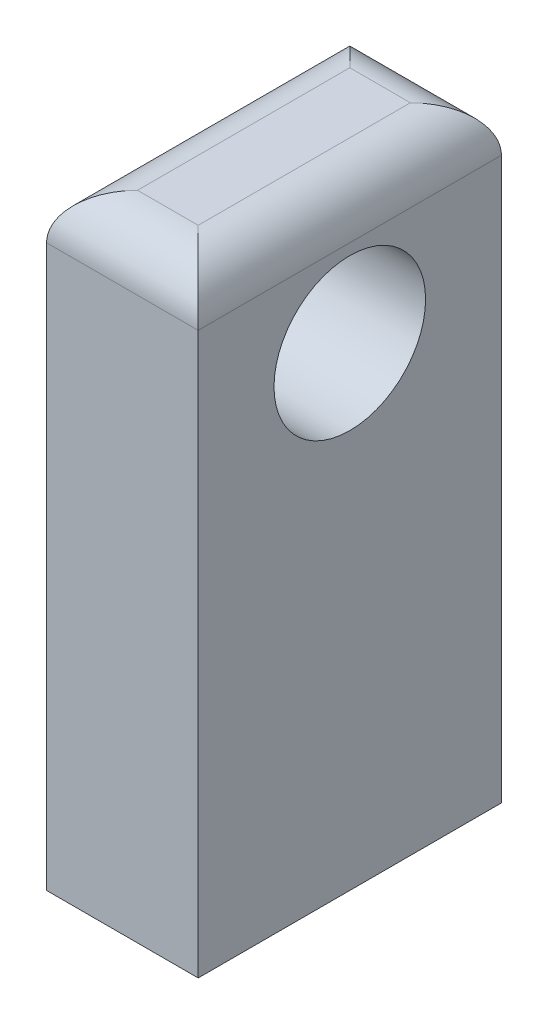
SolidWorks part; units mm, degrees
ref_plane "Front Plane" through (0, 0, 0) normal (0, 0, 1) x (1, 0, 0)
ref_plane "Top Plane" through (0, 0, 0) normal (0, 1, 0) x (1, 0, 0)
ref_plane "Right Plane" through (0, 0, 0) normal (1, 0, 0) x (0, 0, -1)
sketch "Sketch1" plane through (0, 0, 0) normal (1, 0, 0) x (0, 0, -1)
  line L1 (-10, 20) -> (10, 20)
  line L2 (-10, 20) -> (-10, -20)
  line L3 (-10, -20) -> (10, -20)
  line L4 (10, 20) -> (10, -20)
  line L5 (-10, 20) -> (10, -20) construction
  line L6 (-10, -20) -> (10, 20) construction
  circle A0 centre (0, 11.27) radius 5
  point P0 (0, 0)
  point P8 (-10.9419, 26.6411)
  dimension "D2" = 10
  dimension "D1" = 40
  dimension "D3" = 20
  dimension "D4" = 31.27
  dimension "D5" = 10
extrude "Boss-Extrude1" add sketch "Sketch1" along normal blind 10 contours L4 L1 L2 L3 A0
fillet "Fillet1" radius 3 4 edges at (5, 20, -10) (10, 20, 0) (5, 20, 10) (0, 20, 0)
sketch "Sketch2" plane through (0, -20, 0) normal (0, -1, 0) x (1, 0, 0)
  line L0 (10, 10) -> (10, -10) construction
  line L1 (10, 10) -> (0, 10) construction
  point P0 (5, 0)
  dimension "D1" = 5
  dimension "D2" = 10
hole_wizard "Ø3.0mm Dowel Hole1" positions "Sketch2" profile "Sketch3" hole size "Ø3.0" standard "ANSI Metric"
sketch "Sketch3" plane through (5, -20, 0) normal (1, 0, 0) x (0, 0, -1)
  line L0 (0, 0) -> (0, 5.9013)
  line L1 (0, 5.9013) -> (1.5, 5)
  line L2 (1.5, 5) -> (1.5, 0)
  line L5 (1.5, 0) -> (0, 0)
  line L10 (0, 5.9013) -> (-1.5, 5) construction
  line L11 (0, -6.35) -> (0, 107.95) construction
  dimension "Hole Dia." = 3
  dimension "Hole Depth" = 5
  dimension "Drill Angle" = 118
